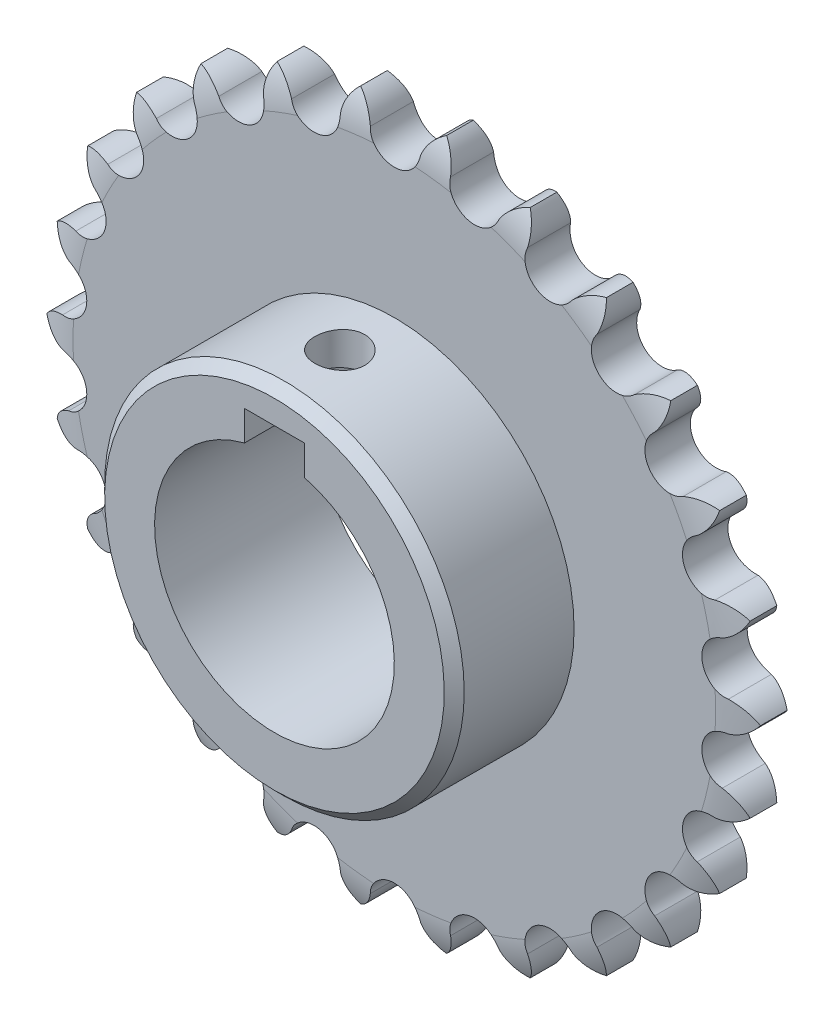
SolidWorks part; units mm, degrees
material "Plain Carbon Steel"
ref_plane "Front Plane" through (0, 0, 0) normal (0, 0, 1) x (1, 0, 0)
ref_plane "Top Plane" through (0, 0, 0) normal (0, 1, 0) x (1, 0, 0)
ref_plane "Right Plane" through (0, 0, 0) normal (1, 0, 0) x (0, 0, -1)
sketch "Sketch1" plane through (0, 0, 0) normal (0, 0, 1) x (1, 0, 0)
  line L0 (0, 49.0689) -> (0, 49.6462) construction
  circle A0 centre (0, 0) radius 19.05
  circle A1 centre (0, 0) radius 53.2867 construction
  point P2 (0, 0)
  point P6 (0, 0.0726)
  arc B0 (6.8354, 56.2947) -> (3.9965, 52.8014) centre (9.5907, 51.1555) ccw
  arc B1 (8.7558, 52.2236) -> (6.8354, 56.2947) centre (2.9303, 51.9642) ccw
  arc B2 (-0.4853, 49.2902) -> (3.9965, 52.8014) centre (0, 53.2867) ccw
  arc B3 (8.7558, 52.2236) -> (12.2671, 47.7418) centre (12.7523, 51.7383) ccw
  arc B4 (20.109, 53.0231) -> (16.5166, 50.3107) centre (21.5543, 47.3738) ccw
  arc B5 (20.9993, 48.6106) -> (20.109, 53.0231) centre (15.281, 49.7529) ccw
  arc B6 (11.3247, 47.974) -> (16.5166, 50.3107) centre (12.7523, 51.7383) ccw
  arc B7 (20.9993, 48.6106) -> (23.336, 43.4188) centre (24.7636, 47.183) ccw
  arc B8 (32.2139, 46.6699) -> (28.0768, 44.8961) centre (32.2652, 40.8389) ccw
  arc B9 (32.0224, 42.1727) -> (32.2139, 46.6699) centre (26.7436, 44.6502) ccw
  arc B10 (22.4766, 43.8698) -> (28.0768, 44.8961) centre (24.7636, 47.183) ccw
  arc B11 (32.0224, 42.1727) -> (33.0487, 36.5724) centre (35.3356, 39.8857) ccw
  arc B12 (42.4467, 37.6045) -> (38.0053, 36.8723) centre (41.1011, 31.9306) ccw
  arc B13 (41.1844, 33.2837) -> (42.4467, 37.6045) centre (36.652, 36.9526) ccw
  arc B14 (32.3222, 37.216) -> (38.0053, 36.8723) centre (35.3356, 39.8857) ccw
  arc B15 (41.1844, 33.2837) -> (40.8407, 27.6006) centre (43.8541, 30.2703) ccw
  arc B16 (50.2126, 26.3536) -> (45.725, 26.7055) centre (47.5482, 21.1666) ccw
  arc B17 (47.953, 22.4605) -> (50.2126, 26.3536) centre (44.4303, 27.1074) ccw
  arc B18 (40.2894, 28.3994) -> (45.725, 26.7055) centre (43.8541, 30.2703) ccw
  arc B19 (47.953, 22.4605) -> (46.2592, 17.0248) centre (49.8239, 18.8957) ccw
  arc B20 (55.0604, 13.5712) -> (50.7874, 14.9868) centre (51.2321, 9.1725) ccw
  arc B21 (51.9347, 10.3319) -> (55.0604, 13.5712) centre (49.6265, 15.6869) ccw
  arc B22 (45.915, 17.9323) -> (50.7874, 14.9868) centre (49.8239, 18.8957) ccw
  arc B23 (51.9347, 10.3319) -> (48.9893, 5.4595) centre (52.8982, 6.423) ccw
  arc B24 (56.7082, 0) -> (52.8982, 2.3971) centre (51.9385, -3.3546) ccw
  arc B25 (52.8982, -2.3971) -> (56.7082, 0) centre (51.9385, 3.3546) ccw
  arc B26 (48.8723, 6.423) -> (52.8982, 2.3971) centre (52.8982, 6.423) ccw
  arc B27 (52.8982, -2.3971) -> (48.8723, -6.423) centre (52.8982, -6.423) ccw
  arc B28 (55.0604, -13.5712) -> (51.9347, -10.3319) centre (49.6265, -15.6869) ccw
  arc B29 (50.7874, -14.9868) -> (55.0604, -13.5712) centre (51.2321, -9.1725) ccw
  arc B30 (48.9893, -5.4595) -> (51.9347, -10.3319) centre (52.8982, -6.423) ccw
  arc B31 (50.7874, -14.9868) -> (45.915, -17.9323) centre (49.8239, -18.8957) ccw
  arc B32 (50.2126, -26.3536) -> (47.953, -22.4605) centre (44.4303, -27.1074) ccw
  arc B33 (45.725, -26.7055) -> (50.2126, -26.3536) centre (47.5482, -21.1666) ccw
  arc B34 (46.2592, -17.0248) -> (47.953, -22.4605) centre (49.8239, -18.8957) ccw
  arc B35 (45.725, -26.7055) -> (40.2894, -28.3994) centre (43.8541, -30.2703) ccw
  arc B36 (42.4467, -37.6045) -> (41.1844, -33.2837) centre (36.652, -36.9526) ccw
  arc B37 (38.0053, -36.8723) -> (42.4467, -37.6045) centre (41.1011, -31.9306) ccw
  arc B38 (40.8407, -27.6006) -> (41.1844, -33.2837) centre (43.8541, -30.2703) ccw
  arc B39 (38.0053, -36.8723) -> (32.3222, -37.216) centre (35.3356, -39.8857) ccw
  arc B40 (32.2139, -46.6699) -> (32.0224, -42.1727) centre (26.7436, -44.6502) ccw
  arc B41 (28.0768, -44.8961) -> (32.2139, -46.6699) centre (32.2652, -40.8389) ccw
  arc B42 (33.0487, -36.5724) -> (32.0224, -42.1727) centre (35.3356, -39.8857) ccw
  arc B43 (28.0768, -44.8961) -> (22.4766, -43.8698) centre (24.7636, -47.183) ccw
  arc B44 (20.109, -53.0231) -> (20.9993, -48.6106) centre (15.281, -49.7529) ccw
  arc B45 (16.5166, -50.3107) -> (20.109, -53.0231) centre (21.5543, -47.3738) ccw
  arc B46 (23.336, -43.4188) -> (20.9993, -48.6106) centre (24.7636, -47.183) ccw
  arc B47 (16.5166, -50.3107) -> (11.3247, -47.974) centre (12.7523, -51.7383) ccw
  arc B48 (6.8354, -56.2947) -> (8.7558, -52.2236) centre (2.9303, -51.9642) ccw
  arc B49 (3.9965, -52.8014) -> (6.8354, -56.2947) centre (9.5907, -51.1555) ccw
  arc B50 (12.2671, -47.7418) -> (8.7558, -52.2236) centre (12.7523, -51.7383) ccw
  arc B51 (3.9965, -52.8014) -> (-0.4853, -49.2902) centre (0, -53.2867) ccw
  arc B52 (-6.8354, -56.2947) -> (-3.9965, -52.8014) centre (-9.5907, -51.1555) ccw
  arc B53 (-8.7558, -52.2236) -> (-6.8354, -56.2947) centre (-2.9303, -51.9642) ccw
  arc B54 (0.4853, -49.2902) -> (-3.9965, -52.8014) centre (0, -53.2867) ccw
  arc B55 (-8.7558, -52.2236) -> (-12.2671, -47.7418) centre (-12.7523, -51.7383) ccw
  arc B56 (-20.109, -53.0231) -> (-16.5166, -50.3107) centre (-21.5543, -47.3738) ccw
  arc B57 (-20.9993, -48.6106) -> (-20.109, -53.0231) centre (-15.281, -49.7529) ccw
  arc B58 (-11.3247, -47.974) -> (-16.5166, -50.3107) centre (-12.7523, -51.7383) ccw
  arc B59 (-20.9993, -48.6106) -> (-23.336, -43.4188) centre (-24.7636, -47.183) ccw
  arc B60 (-32.2139, -46.6699) -> (-28.0768, -44.8961) centre (-32.2652, -40.8389) ccw
  arc B61 (-32.0224, -42.1727) -> (-32.2139, -46.6699) centre (-26.7436, -44.6502) ccw
  arc B62 (-22.4766, -43.8698) -> (-28.0768, -44.8961) centre (-24.7636, -47.183) ccw
  arc B63 (-32.0224, -42.1727) -> (-33.0487, -36.5724) centre (-35.3356, -39.8857) ccw
  arc B64 (-42.4467, -37.6045) -> (-38.0053, -36.8723) centre (-41.1011, -31.9306) ccw
  arc B65 (-41.1844, -33.2837) -> (-42.4467, -37.6045) centre (-36.652, -36.9526) ccw
  arc B66 (-32.3222, -37.216) -> (-38.0053, -36.8723) centre (-35.3356, -39.8857) ccw
  arc B67 (-41.1844, -33.2837) -> (-40.8407, -27.6006) centre (-43.8541, -30.2703) ccw
  arc B68 (-50.2126, -26.3536) -> (-45.725, -26.7055) centre (-47.5482, -21.1666) ccw
  arc B69 (-47.953, -22.4605) -> (-50.2126, -26.3536) centre (-44.4303, -27.1074) ccw
  arc B70 (-40.2894, -28.3994) -> (-45.725, -26.7055) centre (-43.8541, -30.2703) ccw
  arc B71 (-47.953, -22.4605) -> (-46.2592, -17.0248) centre (-49.8239, -18.8957) ccw
  arc B72 (-55.0604, -13.5712) -> (-50.7874, -14.9868) centre (-51.2321, -9.1725) ccw
  arc B73 (-51.9347, -10.3319) -> (-55.0604, -13.5712) centre (-49.6265, -15.6869) ccw
  arc B74 (-45.915, -17.9323) -> (-50.7874, -14.9868) centre (-49.8239, -18.8957) ccw
  arc B75 (-51.9347, -10.3319) -> (-48.9893, -5.4595) centre (-52.8982, -6.423) ccw
  arc B76 (-56.7082, 0) -> (-52.8982, -2.3971) centre (-51.9385, 3.3546) ccw
  arc B77 (-52.8982, 2.3971) -> (-56.7082, 0) centre (-51.9385, -3.3546) ccw
  arc B78 (-48.8723, -6.423) -> (-52.8982, -2.3971) centre (-52.8982, -6.423) ccw
  arc B79 (-52.8982, 2.3971) -> (-48.8723, 6.423) centre (-52.8982, 6.423) ccw
  arc B80 (-55.0604, 13.5712) -> (-51.9347, 10.3319) centre (-49.6265, 15.6869) ccw
  arc B81 (-50.7874, 14.9868) -> (-55.0604, 13.5712) centre (-51.2321, 9.1725) ccw
  arc B82 (-48.9893, 5.4595) -> (-51.9347, 10.3319) centre (-52.8982, 6.423) ccw
  arc B83 (-50.7874, 14.9868) -> (-45.915, 17.9323) centre (-49.8239, 18.8957) ccw
  arc B84 (-50.2126, 26.3536) -> (-47.953, 22.4605) centre (-44.4303, 27.1074) ccw
  arc B85 (-45.725, 26.7055) -> (-50.2126, 26.3536) centre (-47.5482, 21.1666) ccw
  arc B86 (-46.2592, 17.0248) -> (-47.953, 22.4605) centre (-49.8239, 18.8957) ccw
  arc B87 (-45.725, 26.7055) -> (-40.2894, 28.3994) centre (-43.8541, 30.2703) ccw
  arc B88 (-42.4467, 37.6045) -> (-41.1844, 33.2837) centre (-36.652, 36.9526) ccw
  arc B89 (-38.0053, 36.8723) -> (-42.4467, 37.6045) centre (-41.1011, 31.9306) ccw
  arc B90 (-40.8407, 27.6006) -> (-41.1844, 33.2837) centre (-43.8541, 30.2703) ccw
  arc B91 (-38.0053, 36.8723) -> (-32.3222, 37.216) centre (-35.3356, 39.8857) ccw
  arc B92 (-32.2139, 46.6699) -> (-32.0224, 42.1727) centre (-26.7436, 44.6502) ccw
  arc B93 (-28.0768, 44.8961) -> (-32.2139, 46.6699) centre (-32.2652, 40.8389) ccw
  arc B94 (-33.0487, 36.5724) -> (-32.0224, 42.1727) centre (-35.3356, 39.8857) ccw
  arc B95 (-28.0768, 44.8961) -> (-22.4766, 43.8698) centre (-24.7636, 47.183) ccw
  arc B96 (-20.109, 53.0231) -> (-20.9993, 48.6106) centre (-15.281, 49.7529) ccw
  arc B97 (-16.5166, 50.3107) -> (-20.109, 53.0231) centre (-21.5543, 47.3738) ccw
  arc B98 (-23.336, 43.4188) -> (-20.9993, 48.6106) centre (-24.7636, 47.183) ccw
  arc B99 (-16.5166, 50.3107) -> (-11.3247, 47.974) centre (-12.7523, 51.7383) ccw
  arc B100 (-6.8354, 56.2947) -> (-8.7558, 52.2236) centre (-2.9303, 51.9642) ccw
  arc B101 (-3.9965, 52.8014) -> (-6.8354, 56.2947) centre (-9.5907, 51.1555) ccw
  arc B102 (-12.2671, 47.7418) -> (-8.7558, 52.2236) centre (-12.7523, 51.7383) ccw
  arc B103 (-3.9965, 52.8014) -> (0.4853, 49.2902) centre (0, 53.2867) ccw
  dimension "D2" = 38.1
  dimension "D3" = 106.5734
  dimension "D1" = 26
sketch_block_instance "Block1-1"
sketch_block "Block1"
sketch_block_instance "Block1-100"
sketch_block_instance "Block1-101"
sketch_block_instance "Block1-102"
sketch_block_instance "Block1-103"
sketch_block_instance "Block1-104"
sketch_block_instance "Block1-105"
sketch_block_instance "Block1-106"
sketch_block_instance "Block1-107"
sketch_block_instance "Block1-108"
sketch_block_instance "Block1-109"
sketch_block_instance "Block1-110"
sketch_block_instance "Block1-111"
sketch_block_instance "Block1-112"
sketch_block_instance "Block1-113"
sketch_block_instance "Block1-114"
sketch_block_instance "Block1-115"
sketch_block_instance "Block1-116"
sketch_block_instance "Block1-117"
sketch_block_instance "Block1-118"
sketch_block_instance "Block1-119"
sketch_block_instance "Block1-120"
sketch_block_instance "Block1-121"
sketch_block_instance "Block1-122"
sketch_block_instance "Block1-123"
sketch_block_instance "Block1-124"
extrude "Boss-Extrude1" add sketch "Sketch1" along normal blind 7.2136 contours B103 B101 B100 B102 B99 B97 B96 B98 B95 B93 B92 B94 B91 B89 B88 B90 B87 B85 B84 B86 B83 B81 B80 B82 B79 B77 B76 B78 B75 B73 B72 B74 B71 B69 B68 B70 B67 B65 B64 B66 B63 B61 B60 B62 B59 B57 B56 B58 B55 B53 B52
sketch "Sketch2" plane through (0, 0, 0) normal (1, 0, 0) x (0, 0, -1)
  line L0 (0, 0) -> (-31.0798, 0) construction
  line L1 (-7.2136, 28.575) -> (-26.2636, 28.575)
  line L2 (-26.2636, 28.575) -> (-26.2636, 19.05)
  line L3 (-26.2636, 19.05) -> (-7.2136, 19.05)
  line L4 (-7.2136, 19.05) -> (-7.2136, 28.575)
  line L5 (-7.2136, 22.4605) -> (-7.2136, 14.8698) construction
  dimension "D1" = 19.05
  dimension "D2" = 38.1
  dimension "D3" = 57.15
revolve "Revolve1" add sketch "Sketch2" angle 360 about L0
chamfer "Chamfer1" distance 1.5875 angle 45 1 edges at (0, 28.575, 26.2636)
sketch "Sketch3" plane through (0, 0, 26.2636) normal (0, 0, 1) x (1, 0, 0)
  line L0 (0, 0) -> (0, 33.7073) construction
  line L2 (-4.7625, 18.4451) -> (4.7625, 18.4451)
  line L3 (-4.7625, 18.4451) -> (-4.7625, 23.2076)
  line L4 (-4.7625, 23.2076) -> (4.7625, 23.2076)
  line L5 (4.7625, 18.4451) -> (4.7625, 23.2076)
  circle A1 centre (0, 0) radius 19.05 construction
  dimension "D1" = 9.525
  dimension "D2" = 4.7625
extrude "Cut-Extrude1" cut sketch "Sketch3" against normal up to surface (26.2636 mm away) up to face at (0, 0, 0)
hole_wizard "3/8-16 Tapped Hole1" positions "Sketch7" profile "Sketch8" tap size "3/8-16" standard "ANSI Inch"
sketch "Sketch7" plane through (0, 23.2076, 0) normal (0, -1, 0) x (-1, 0, 0)
  line L0 (4.7625, 0) -> (-4.7625, 0) construction
  point P0 (0, -15.875)
  dimension "D1" = 15.875
sketch "Sketch8" plane through (0, 23.2076, 15.875) normal (1, 0, 0) x (0, 0, -1)
  line L0 (0, 0) -> (0, 9.4967)
  line L1 (0, 9.4967) -> (3.9687, 7.112)
  line L2 (3.9687, 7.112) -> (3.9687, 0)
  line L5 (3.9687, 0) -> (0, 0)
  line L10 (0, 9.4967) -> (-3.9688, 7.112) construction
  line L11 (0, -6.35) -> (0, 107.95) construction
  dimension "Tap Drill Dia." = 7.9375
  dimension "Tap Drill Depth" = 7.112
  dimension "Drill Angle" = 118
cosmetic thread "Hole Thread1" parameters "D1"=5.4663, "D2"=9.525
sketch "Sketch9" plane through (0, 0, 0) normal (1, 0, 0) x (0, 0, -1)
  line L0 (-7.2136, 53.0231) -> (-7.2136, 48.6106) construction
  line L1 (-5.6261, 56.896) -> (-7.5931, 56.896)
  line L2 (-5.6261, 57.2967) -> (-5.6261, 48.1883) construction
  line L3 (-7.2136, 56.2947) -> (-7.2136, 52.2236) construction
  line L4 (-7.5931, 56.896) -> (-7.5931, 50.419)
  line L5 (-7.5931, 50.419) -> (-7.2136, 50.419)
  line L6 (-3.6068, 56.2947) -> (-3.6068, 52.1715) construction
  line L7 (0.3795, 50.419) -> (0, 50.419)
  line L8 (-1.5875, 56.896) -> (0.3795, 56.896)
  line L9 (0.3795, 56.896) -> (0.3795, 50.419)
  line L10 (0, 52.2236) -> (0, 56.2947) construction
  line L14 (0, 0) -> (0, 34.6896) construction
  line L15 (0, 0) -> (-36.7155, 0) construction
  arc A0 (-7.2136, 50.419) -> (-5.6261, 56.896) centre (5.4823, 50.7403) cw
  arc A1 (0, 50.419) -> (-1.5875, 56.896) centre (-12.6959, 50.7403) ccw
  dimension "D3" = 12.7
  dimension "D1" = 50.419
  dimension "D2" = 1.5875
  dimension "D4" = 56.896
revolve "Cut-Revolve1" cut sketch "Sketch9" angle 360 about L15
sketch "Sketch10" plane through (0, 0, 7.2136) normal (0, 0, 1) x (1, 0, 0)
  circle A0 centre (0, 53.2867) radius 4.0251 construction
